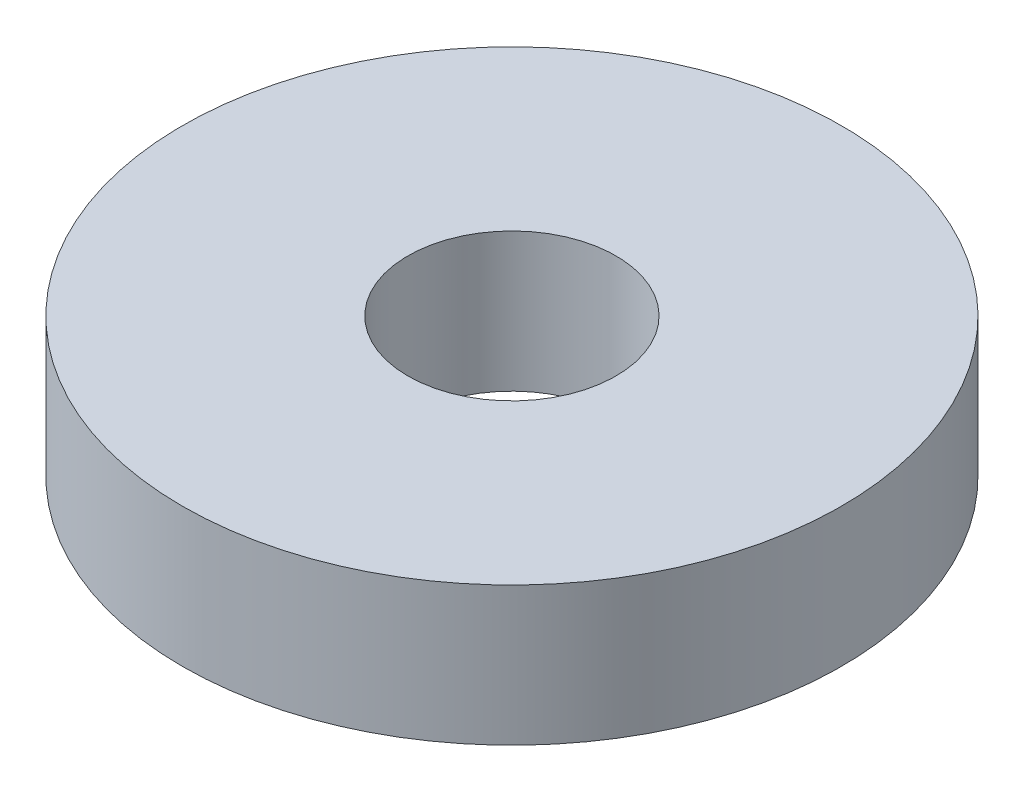
SolidWorks part; units mm, degrees
material "6061 合金"
ref_plane "前视基准面" through (0, 0, 0) normal (0, 0, 1) x (1, 0, 0)
ref_plane "上视基准面" through (0, 0, 0) normal (0, 1, 0) x (1, 0, 0)
ref_plane "右视基准面" through (0, 0, 0) normal (1, 0, 0) x (0, 0, -1)
other "Configuration Table"
sketch "草图1" plane through (0, 0, 0) normal (0, 1, 0) x (1, 0, 0)
  circle A0 centre (0, 0) radius 3
  circle A1 centre (0, 0) radius 9.5
  dimension "D1" = 19
  dimension "D2" = 6
extrude "凸台-拉伸1" add sketch "草图1" along normal blind 4
